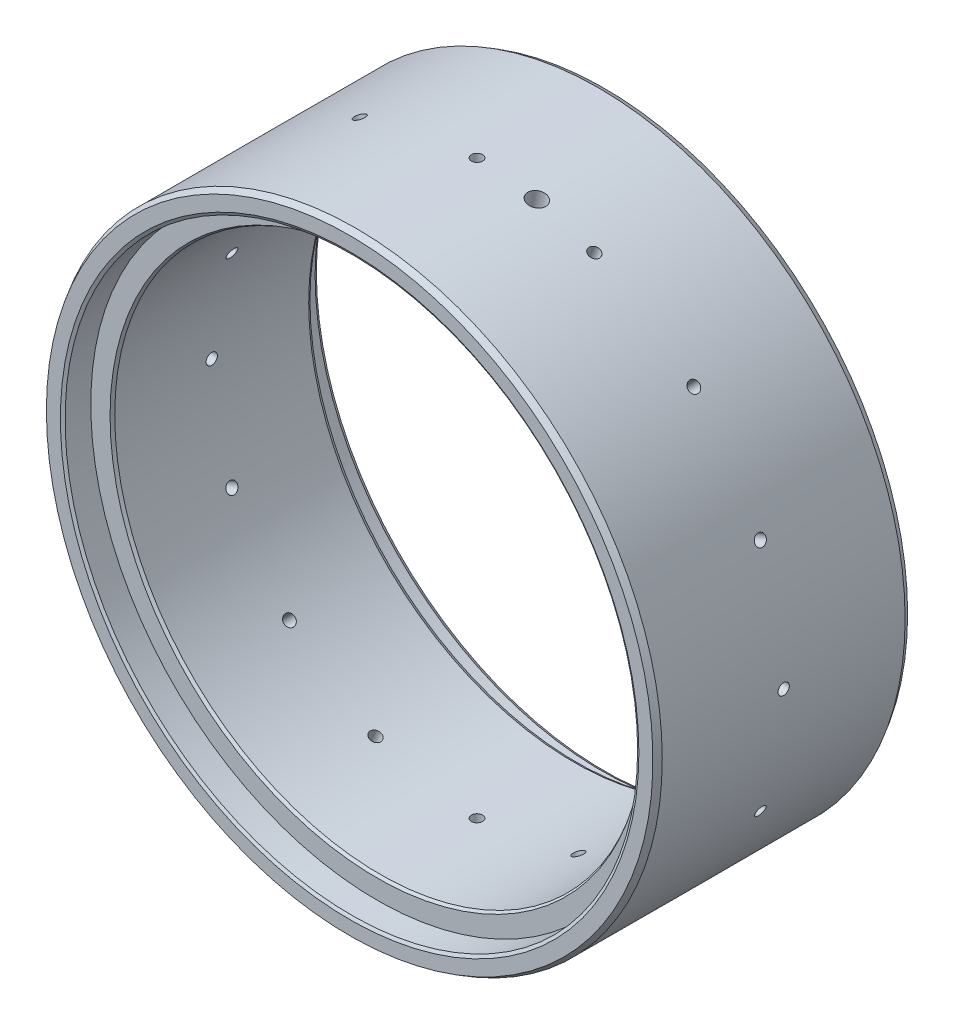
SolidWorks part; units mm, degrees
material "6061-T6 (SS)"
ref_plane "Front Plane" through (0, 0, 0) normal (0, 0, 1) x (1, 0, 0)
ref_plane "Top Plane" through (0, 0, 0) normal (0, 1, 0) x (1, 0, 0)
ref_plane "Right Plane" through (0, 0, 0) normal (1, 0, 0) x (0, 0, -1)
sketch "Sketch1" plane through (0, 0, 0) normal (0, 0, 1) x (1, 0, 0)
  circle A0 centre (0, 0) radius 68.199
  circle A1 centre (0, 0) radius 58.9915
  dimension "D1" = 136.398
  dimension "D2" = 117.983
extrude "Extrude1" add sketch "Sketch1" along normal mid plane 56.642
sketch "Sketch11" plane through (0, 0, -28.321) normal (0, 0, -1) x (-1, 0, 0)
  circle A0 centre (0, 0) radius 63.66
  dimension "D1" = 127.32
extrude "Extrude2" cut sketch "Sketch11" against normal blind 6.096
mirror "Mirror1" about plane through (0, 0, 0) normal (0, 0, 1) of "Extrude2"
sketch "Sketch2" plane through (0, 0, 0) normal (0, 0, 1) x (1, 0, 0)
  line L0 (0, 0) -> (0, 68.199) construction
  line L1 (0, 0) -> (13.305, 66.8886) construction
  circle A0 centre (0, 0) radius 68.199 construction
  dimension "D1" = 11.25
ref_plane "Plane1" through (0, 68.199, 0) normal (0, 1, 0) x (-1, 0, 0)
ref_plane "Plane2" through (13.305, 66.8886, 0) normal (0.1951, 0.9808, 0) x (-0.9808, 0.1951, 0)
sketch "Sketch3" plane through (0, 68.199, 0) normal (0, 1, 0) x (-1, 0, 0)
  line L0 (0, 0) -> (0, 28.321) construction
  line L1 (0, 28.321) -> (0, -28.321) construction
  line L2 (68.199, 28.321) -> (-68.199, 28.321) construction
  point P7 (0, 14.1605)
sketch "Sketch6" plane through (13.305, 66.8886, 0) normal (0.1951, 0.9808, 0) x (-0.9808, 0.1951, 0)
  line L0 (0, 0) -> (0, 28.321) construction
  line L1 (68.199, 28.321) -> (-68.199, 28.321) construction
  point P5 (0, 14.1605)
hole_wizard "Tap Drill for M3x0.5 Tap1" positions "Sketch5" profile "Sketch4" hole size "M3x0.5" standard "Ansi Metric"
sketch "Sketch5" plane through (0, 68.199, 0) normal (0, 1, 0) x (-1, 0, 0)
  point P6 (0, 0)
sketch "Sketch4" plane through (0, 68.199, 0) normal (1, 0, 0) x (0, 0, 1)
  line L0 (0, 0) -> (0, 10.9111)
  line L1 (0, 10.9111) -> (1.25, 10.16)
  line L2 (1.25, 10.16) -> (1.25, 0)
  line L5 (1.25, 0) -> (0, 0)
  line L10 (0, 10.9111) -> (-1.25, 10.16) construction
  line L11 (0, -6.35) -> (0, 107.95) construction
  dimension "Hole Dia." = 2.5
  dimension "Hole Depth" = 10.16
  dimension "Drill Angle" = 118
pattern_circular "CirPattern1" count 16 over 360 about axis through (0, 0, 28.321) along (0, 0, -1) of "Tap Drill for M3x0.5 Tap1"
chamfer "Chamfer1" distance 0.381 angle 60 4 edges at (-58.9915, 0, -22.225) (-63.66, 0, 28.321) (58.9915, 0, 22.225) (-63.66, 0, -28.321)
chamfer "Chamfer3" distance 0.762 angle 60 2 edges at (68.199, 0, 28.321) (68.199, 0, -28.321)
hole_wizard "#10-32 Tapped Hole1" positions "Sketch13" profile "Sketch14" tap size "#10-32" standard "Ansi Inch"
sketch "Sketch13" plane through (13.305, 66.8886, 0) normal (0.1951, 0.9808, 0) x (-0.9808, 0.1951, 0)
  point P1 (0, 0)
sketch "Sketch14" plane through (13.305, 66.8886, 0) normal (0, 0, 1) x (-0.9808, 0.1951, 0)
  line L0 (0, 0) -> (0, 14.8277)
  line L1 (0, 14.8277) -> (2.0193, 13.6144)
  line L2 (2.0193, 13.6144) -> (2.0193, 0)
  line L5 (2.0193, 0) -> (0, 0)
  line L10 (0, 14.8277) -> (-2.0193, 13.6144) construction
  line L11 (0, -6.35) -> (0, 107.95) construction
  dimension "Tap Drill Dia." = 4.0386
  dimension "Tap Drill Depth" = 13.6144
  dimension "Drill Angle" = 118
cosmetic thread "Hole Thread1" parameters "D1"=9.2421, "D2"=4.826
